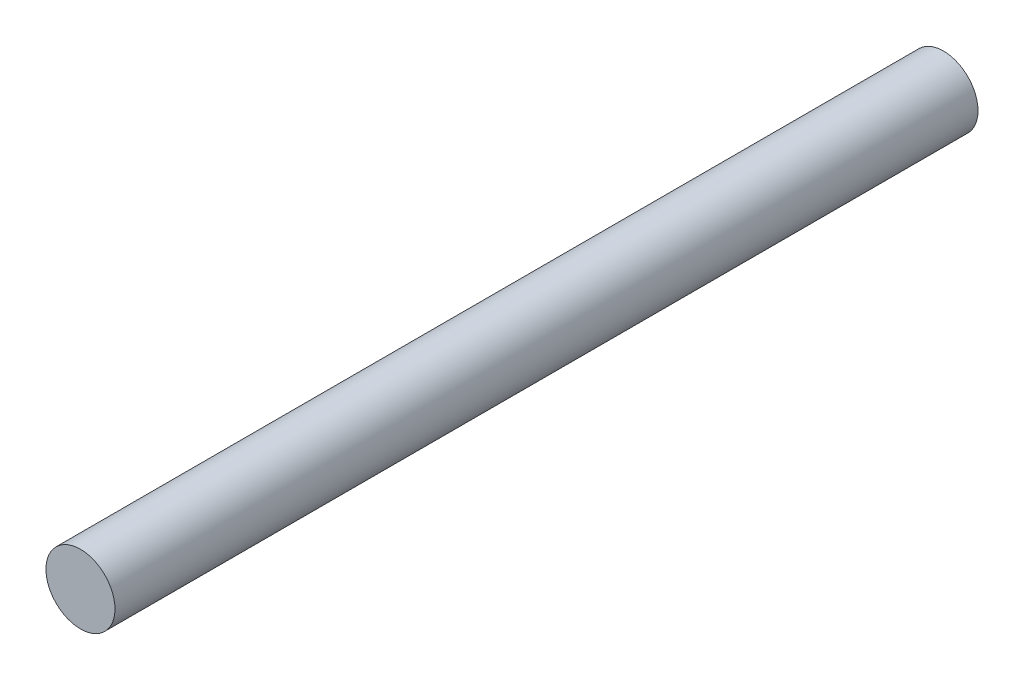
SolidWorks part; units mm, degrees
ref_plane "Front Plane" through (0, 0, 0) normal (0, 0, 1) x (1, 0, 0)
ref_plane "Top Plane" through (0, 0, 0) normal (0, 1, 0) x (1, 0, 0)
ref_plane "Right Plane" through (0, 0, 0) normal (1, 0, 0) x (0, 0, -1)
sketch "Sketch1" plane through (0, 0, 0) normal (0, 0, 1) x (1, 0, 0)
  circle A0 centre (0, 0) radius 0.8
  dimension "D1" = 1.6
extrude "Boss-Extrude1" add sketch "Sketch1" along normal blind 20
